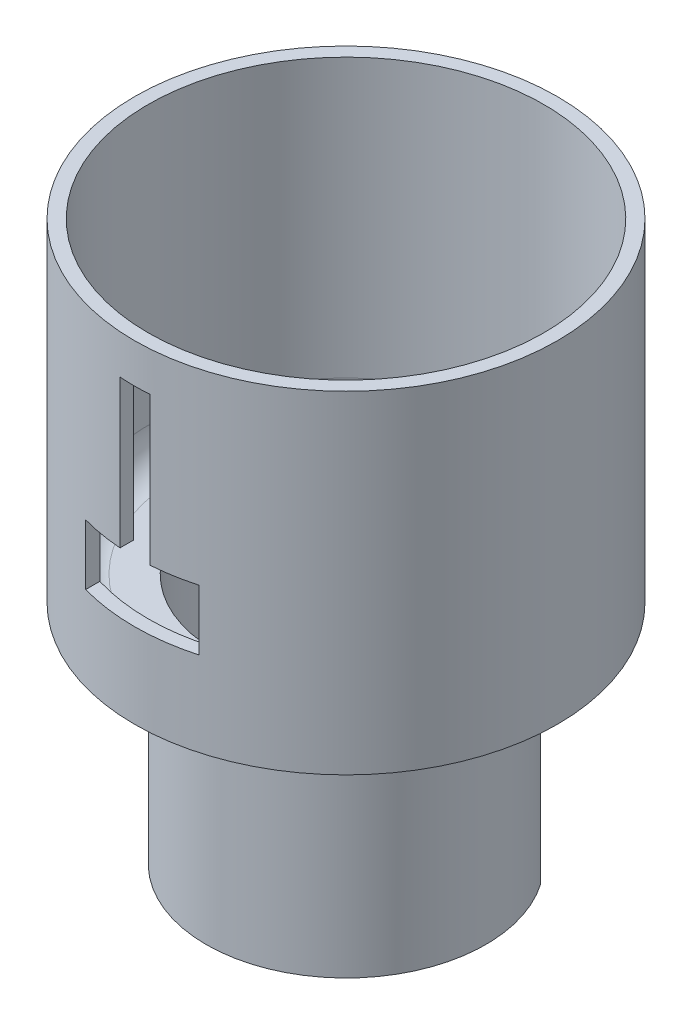
SolidWorks part; units mm, degrees
ref_plane "Front Plane" through (0, 0, 0) normal (0, 0, 1) x (1, 0, 0)
ref_plane "Top Plane" through (0, 0, 0) normal (0, 1, 0) x (1, 0, 0)
ref_plane "Right Plane" through (0, 0, 0) normal (1, 0, 0) x (0, 0, -1)
sketch "Sketch1" plane through (0, 0, 0) normal (0, 1, 0) x (1, 0, 0)
  circle A0 centre (0, 0) radius 17.78
  dimension "D1" = 35.56
extrude "Boss-Extrude1" add sketch "Sketch1" along normal blind 27.94
sketch "Sketch2" plane through (0, 0, 0) normal (0, 1, 0) x (1, 0, 0)
  circle A0 centre (0, 0) radius 11.7602
  dimension "D1" = 23.5204
extrude "Boss-Extrude2" add sketch "Sketch2" against normal blind 19.05
sketch "Sketch3" plane through (0, 27.94, 0) normal (0, 1, 0) x (1, 0, 0)
  circle A0 centre (0, 0) radius 16.637
  dimension "D1" = 33.274
extrude "Cut-Extrude1" cut sketch "Sketch3" against normal blind 25.908
sketch "Sketch4" plane through (0, 2.032, 0) normal (0, 1, 0) x (1, 0, 0)
  circle A0 centre (0, 0) radius 11.049
  dimension "D1" = 22.098
extrude "Cut-Extrude2" cut sketch "Sketch4" against normal blind 6.858
sketch "Sketch5" plane through (0, 0, 0) normal (1, 0, 0) x (0, 0, -1)
  line L1 (11.7602, -19.05) -> (6.7056, -19.05)
  line L2 (11.7602, -19.05) -> (11.7602, -6.35)
  line L3 (11.7602, -6.35) -> (6.7056, -6.35)
  line L4 (6.7056, -19.05) -> (6.7056, -6.35)
  dimension "D1" = 12.7
  dimension "D2" = 6.7056
extrude "Cut-Extrude3" cut sketch "Sketch5" against normal through all both and the other way through all
sketch "Sketch7" plane through (0, 0, 0) normal (1, 0, 0) x (0, 0, -1)
  line L0 (11.7602, -6.35) -> (11.7602, -14.7885)
  line L1 (11.7602, -14.7885) -> (6.7056, -19.05)
  line L2 (6.7056, -19.05) -> (6.7056, -16.3922)
  line L3 (6.7056, -16.3922) -> (9.7282, -13.8439)
  line L4 (9.7282, -13.8439) -> (9.7282, -6.35)
  line L5 (9.7282, -6.35) -> (11.7602, -6.35)
  dimension "D1" = 2.032
  dimension "D3" = 2.032
ref_plane "Plane1" through (-9.6611, -19.05, -6.7056) normal (1, 0, 0) x (0, 0, -1)
extrude "Boss-Extrude3" add sketch "Sketch7" along normal blind 0.9525 and the other way blind 0.9525
sketch "Sketch9" plane through (0, -4.826, 0) normal (0, 1, 0) x (1, 0, 0)
  line L0 (-9.6195, 5.4356) -> (9.6195, 5.4356)
  line L5 (-9.6611, 6.7056) -> (9.6611, 6.7056) construction
  circle A0 centre (0, 0) radius 11.049
  circle M3 centre (0, 0) radius 11.049
  dimension "D1" = 22.098
  dimension "D2" = 1.27
extrude "Cut-Extrude4" cut sketch "Sketch9" against normal blind 12.192 contours L0 M3
fillet "Fillet1" radius 2.54 1 edges at (0, 2.032, 16.637)
sketch "Sketch11" plane through (0, 0, 0) normal (0, 0, 1) x (1, 0, 0)
  line L2 (-2.5327, 7.112) -> (-4.7625, 7.112)
  line L3 (-4.7625, 7.112) -> (-4.7625, 12.192)
  line L4 (-4.7625, 12.192) -> (-1.27, 12.192)
  line L6 (1.27, 12.192) -> (4.7625, 12.192)
  line L7 (4.7625, 12.192) -> (4.7625, 7.112)
  line L8 (4.7625, 7.112) -> (2.5327, 7.112)
  line L10 (2.5327, 7.112) -> (-2.5327, 7.112)
  line L11 (1.27, 12.192) -> (1.27, 24.638)
  line L12 (1.27, 24.638) -> (-1.27, 24.638)
  line L13 (-1.27, 24.638) -> (-1.27, 12.192)
  line L14 (16.637, 27.94) -> (-16.637, 27.94) construction
  line L15 (-16.637, 4.572) -> (16.637, 4.572) construction
  point P0 (0, 7.112)
  point P15 (0, 0)
  point P16 (0, 7.112)
  dimension "D1" = 2.54
  dimension "D2" = 9.525
  dimension "D3" = 5.08
  dimension "D4" = 3.302
  dimension "D5" = 2.54
extrude "Cut-Extrude5" cut sketch "Sketch11" along normal through all
sketch "Sketch12" plane through (0, -19.05, 0) normal (0, -1, 0) x (1, 0, 0)
  circle A0 centre (0, 0) radius 2.54
  dimension "D1" = 5.08
extrude "Cut-Extrude6" cut sketch "Sketch12" against normal up to next
sketch "Sketch13" plane through (0, -17.018, 0) normal (0, 1, 0) x (1, 0, 0)
  point P0 (0, 0)
